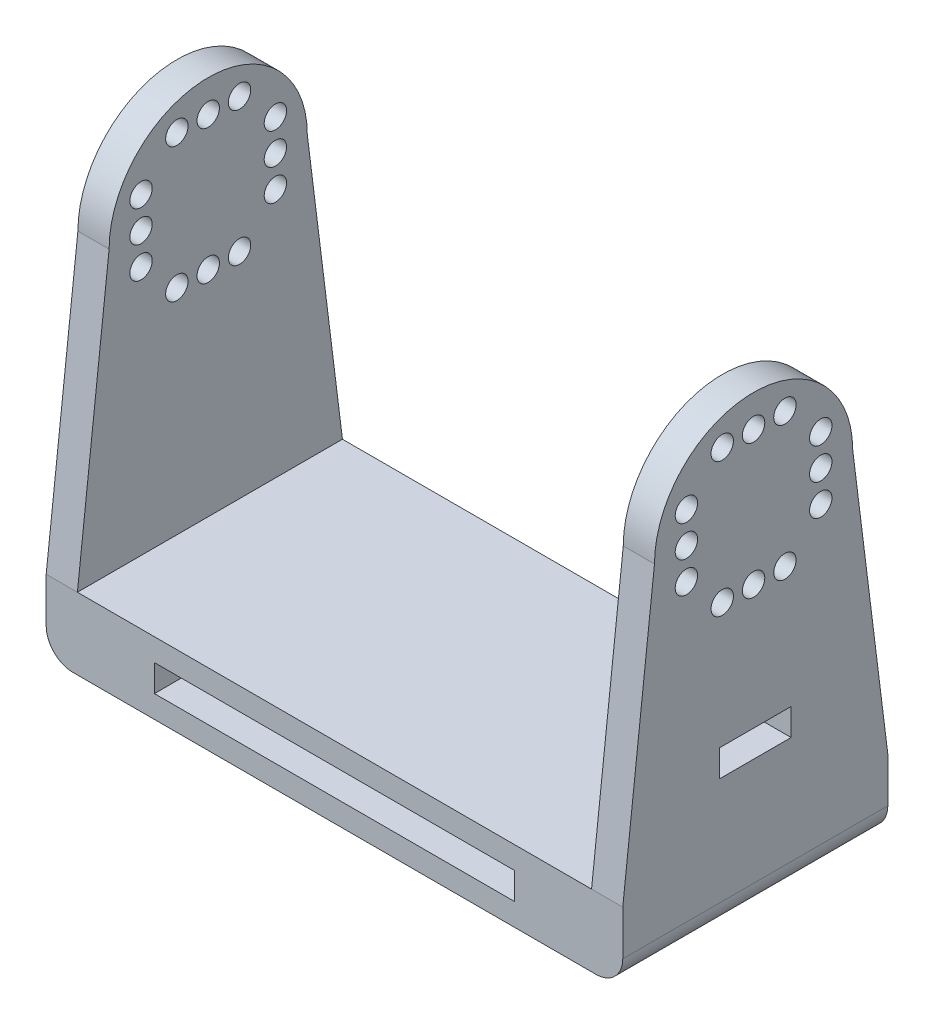
SolidWorks part; units mm, degrees
ref_plane "Front Plane" through (0, 0, 0) normal (0, 0, 1) x (1, 0, 0)
ref_plane "Top Plane" through (0, 0, 0) normal (0, 1, 0) x (1, 0, 0)
ref_plane "Right Plane" through (0, 0, 0) normal (1, 0, 0) x (0, 0, -1)
sketch "Sketch2" plane through (0, 0, 0) normal (0, 1, 0) x (1, 0, 0)
  line L1 (-52.4481, 29.2191) -> (11.9219, 29.2191)
  line L2 (-52.4481, 29.2191) -> (-52.4481, -0.3709)
  line L3 (-52.4481, -0.3709) -> (11.9219, -0.3709)
  line L4 (11.9219, 29.2191) -> (11.9219, -0.3709)
extrude "Boss-Extrude1" add sketch "Sketch2" along normal blind 8
sketch "Sketch3" plane through (0, 8, 0) normal (0, 1, 0) x (1, 0, 0)
  line L0 (-52.4481, 29.2191) -> (-48.9631, 29.2191)
  line L1 (11.9219, 29.2191) -> (-52.4481, 29.2191) construction
  line L2 (-48.9631, 29.2191) -> (-48.9631, -0.3709)
  line L3 (-52.4481, -0.3709) -> (11.9219, -0.3709) construction
  line L4 (-48.9631, -0.3709) -> (-52.4481, -0.3709)
  line L5 (-52.4481, -0.3709) -> (-52.4481, 29.2191)
  line L6 (11.9219, 29.2191) -> (8.4369, 29.2191) construction
  line L7 (8.4369, 29.2191) -> (8.4369, -0.3709) construction
  line L8 (8.4369, -0.3709) -> (11.9219, -0.3709) construction
  line L9 (11.9219, -0.3709) -> (11.9219, 29.2191) construction
  line L10 (11.9219, -0.3709) -> (11.9219, 29.2191) construction
  line L11 (8.4369, 29.2191) -> (11.9219, 29.2191)
  line L12 (11.9219, 29.2191) -> (11.9219, -0.3709)
  line L13 (11.9219, -0.3709) -> (8.4369, -0.3709)
  line L14 (8.4369, -0.3709) -> (8.4369, 29.2191)
extrude "Boss-Extrude2" add sketch "Sketch3" along normal blind 50
fillet "Fillet2" radius 3 2 edges at (11.9219, 0, -14.4241) (-52.4481, 0, -14.4241)
sketch "Sketch4" plane through (-52.4481, 0, 0) normal (-1, 0, 0) x (0, 0, 1)
  line L3 (-14.2332, 39.4033) -> (-6.7332, 39.4033) construction
  line L4 (-6.7332, 39.4033) -> (-14.2332, 39.4033) construction
  line L5 (-14.2332, 39.4033) -> (-21.7332, 39.4033) construction
  line L6 (-21.7332, 39.4033) -> (-14.2332, 39.4033) construction
  line L7 (-14.2332, 39.4033) -> (-14.2332, 31.9033) construction
  line L8 (-14.2332, 31.9033) -> (-14.2332, 39.4033) construction
  line L9 (-14.2332, 39.4033) -> (-14.2332, 46.9033) construction
  line L10 (-6.7332, 39.4033) -> (-6.7332, 42.9033) construction
  line L11 (-6.7332, 42.9033) -> (-6.7332, 39.4033) construction
  line L12 (-6.7332, 39.4033) -> (-6.7332, 35.9033) construction
  line L13 (-14.2332, 46.9033) -> (-10.7332, 46.9033) construction
  line L14 (-14.2332, 46.9033) -> (-17.7332, 46.9033) construction
  line L15 (-14.2332, 31.9033) -> (-10.7332, 31.9033) construction
  line L16 (-14.2332, 31.9033) -> (-17.7332, 31.9033) construction
  line L17 (-29.2191, 3) -> (-29.2191, 8) construction
  line L18 (-21.7332, 39.4033) -> (-21.7332, 42.9033) construction
  line L20 (-21.7332, 39.4033) -> (-21.7332, 35.9033) construction
  line L21 (-29.2191, 8) -> (0.3709, 8) construction
  line L22 (0.3709, 58) -> (0.3709, 3) construction
  line L23 (-25.2969, 39.4033) -> (-29.2191, 8)
  line L24 (-29.2191, 8) -> (0.3709, 8)
  line L25 (0.3709, 8) -> (-3.1695, 39.4033)
  circle A0 centre (-14.2332, 39.4033) radius 11.0637
  circle A1 centre (-6.7332, 39.4033) radius 1.25
  circle A2 centre (-6.7332, 35.9033) radius 1.25
  circle A3 centre (-6.7332, 42.9033) radius 1.25
  circle A4 centre (-14.2332, 46.9033) radius 1.25
  circle A5 centre (-14.2332, 31.9033) radius 1.25
  circle A6 centre (-10.7332, 46.9033) radius 1.25
  circle A7 centre (-17.7332, 46.9033) radius 1.25
  circle A8 centre (-10.7332, 31.9033) radius 1.25
  circle A9 centre (-17.7332, 31.9033) radius 1.25
  circle A10 centre (-21.7332, 39.4033) radius 1.25
  circle A11 centre (-21.7332, 42.9033) radius 1.25
  circle A12 centre (-21.7332, 35.9033) radius 1.25
  line M1 (-29.2191, 58) -> (-29.2191, 3)
  line M3 (0.3709, 3) -> (0.3709, 58)
  line M4 (0.3709, 58) -> (-29.2191, 58)
extrude "Cut-Extrude8" cut sketch "Sketch4" against normal blind 70 contours A0 L25 L23 M3 M4 M1 | A11 | A10 | A12 | A9 | A8 | A2 | A1 | A3 | A6 | A7 | A4 | A5
sketch "Sketch12" plane through (11.9219, 0, 0) normal (1, 0, 0) x (0, 0, -1)
  line L0 (14.4241, 3) -> (14.4241, 18) construction
  line L1 (-0.3709, 3) -> (29.2191, 3) construction
  line L2 (14.4241, 18) -> (10.4241, 18)
  line L3 (10.4241, 18) -> (18.4241, 18)
  line L4 (18.4241, 18) -> (18.4241, 15)
  line L5 (18.4241, 15) -> (10.4241, 15)
  line L6 (10.4241, 15) -> (10.4241, 18)
sketch "Sketch27" plane through (0, 0, 0.3709) normal (0, 0, 1) x (1, 0, 0)
  line L0 (-20.2631, 0) -> (-20.2631, 8) construction
  line L1 (-49.4481, 0) -> (8.9219, 0) construction
  line L2 (-48.9631, 8) -> (8.4369, 8) construction
  line L3 (-20.2631, 8) -> (-20.2631, 4) construction
  line L4 (-20.2631, 4) -> (-40.3631, 4) construction
  line L5 (-40.3631, 4) -> (-40.3631, 2.5) construction
  line L6 (-40.3631, 2.5) -> (-40.3631, 5.5) construction
  line L7 (-40.3631, 5.5) -> (-0.1631, 5.5) construction
  line L8 (-0.1631, 5.5) -> (-0.1631, 2.5) construction
  line L9 (-0.1631, 2.5) -> (-40.3631, 2.5) construction
  line L10 (-0.1631, 5.5) -> (-0.1631, 2.5)
  line L11 (-0.1631, 2.5) -> (-40.3631, 2.5)
  line L12 (-40.3631, 2.5) -> (-40.3631, 5.5)
  line L13 (-40.3631, 5.5) -> (-0.1631, 5.5)
extrude "Cut-Extrude14" cut sketch "Sketch27" against normal blind 12.295
sketch "Sketch30" plane through (0, 0, -29.2191) normal (0, 0, -1) x (-1, 0, 0)
  line L0 (20.2631, 8) -> (20.2631, 0) construction
  line L1 (-8.4369, 8) -> (48.9631, 8) construction
  line L2 (-8.9219, 0) -> (49.4481, 0) construction
  line L3 (20.2631, 0) -> (20.2631, 4) construction
  line L4 (20.2631, 4) -> (0.1631, 4) construction
  line L5 (0.1631, 4) -> (0.1631, 2.5) construction
  line L6 (0.1631, 2.5) -> (0.1631, 5.5) construction
  line L7 (0.1631, 5.5) -> (40.3631, 5.5) construction
  line L8 (40.3631, 5.5) -> (40.3631, 2.5) construction
  line L9 (40.3631, 2.5) -> (0.1631, 2.5) construction
  line L10 (40.3631, 5.5) -> (40.3631, 2.5)
  line L11 (40.3631, 2.5) -> (0.1631, 2.5)
  line L12 (0.1631, 2.5) -> (0.1631, 5.5)
  line L13 (0.1631, 5.5) -> (40.3631, 5.5)
extrude "Cut-Extrude15" cut sketch "Sketch30" against normal blind 12.295
extrude "Cut-Extrude16" cut sketch "Sketch12" against normal blind 60 contours L5 L0 L2 L6 | L0 L5 L4 L3
